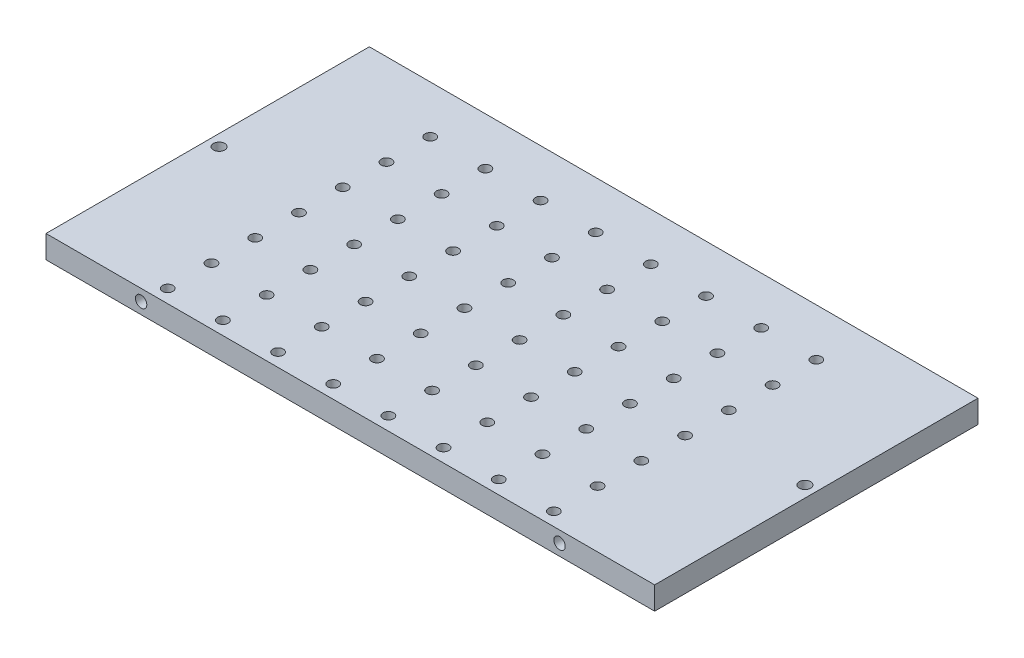
SolidWorks part; units mm, degrees
ref_plane "Plan de face" through (0, 0, 0) normal (0, 0, 1) x (1, 0, 0)
ref_plane "Plan de dessus" through (0, 0, 0) normal (0, 1, 0) x (1, 0, 0)
ref_plane "Plan de droite" through (0, 0, 0) normal (1, 0, 0) x (0, 0, -1)
sketch "Esquisse1" plane through (0, 0, 0) normal (0, 1, 0) x (1, 0, 0)
  line L1 (-80, -42.5) -> (80, -42.5)
  line L2 (-80, -42.5) -> (-80, 42.5)
  line L3 (-80, 42.5) -> (80, 42.5)
  line L4 (80, -42.5) -> (80, 42.5)
  line L5 (-80, -42.5) -> (80, 42.5) construction
  line L6 (-80, 42.5) -> (80, -42.5) construction
  point P0 (0, 0)
  dimension "D1" = 85
  dimension "D2" = 160
extrude "Boss.-Extru.1" add sketch "Esquisse1" along normal blind 6
sketch "Esquisse2" plane through (0, 0, 42.5) normal (0, 0, 1) x (1, 0, 0)
  line L0 (-80, 3) -> (29.6548, 3) construction
  line L3 (-80, 6) -> (-80, 0) construction
  line L5 (0, 0) -> (0, 17.0048) construction
  circle A0 centre (-55, 3) radius 1.5
  circle A1 centre (55, 3) radius 1.5
  dimension "D2" = 25
  dimension "D3" = 3
extrude "Enlèv. mat.-Extru.1" cut sketch "Esquisse2" against normal up to surface (85 mm away) up to face at (0, 3, -42.5)
sketch "Esquisse3" plane through (0, 0, 0) normal (0, 1, 0) x (1, 0, 0)
  line L1 (-55, 3.5) -> (10, 3.5) construction
  line L2 (-55, 3.5) -> (-55, 33.5) construction
  line L3 (-55, 33.5) -> (10, 33.5) construction
  line L4 (10, 3.5) -> (10, 33.5) construction
  line L5 (-55, 3.5) -> (10, 33.5) construction
  line L6 (-55, 33.5) -> (10, 3.5) construction
  line L7 (80, 42.5) -> (-80, 42.5) construction
  line L8 (-80, 42.5) -> (-80, -42.5) construction
  circle A0 centre (-51.5, 30) radius 1.375
  point P0 (-22.5, 18.5)
  dimension "D3" = 2.75
  dimension "D4" = 3.5
  dimension "D1" = 65
  dimension "D2" = 30
  dimension "D5" = 3.5
  dimension "D6" = 9
  dimension "D7" = 25
extrude "Enlèv. mat.-Extru.2" cut sketch "Esquisse3" along normal up to surface (6 mm away) up to face at (0, 6, 0)
pattern_linear "Répétition linéaire1" count 7 spacing 11.5 along (0, 0, 1) count 8 spacing 14.5 along (1, 0, 0) of "Enlèv. mat.-Extru.2"
sketch "Esquisse4" plane through (0, 0, 0) normal (0, 1, 0) x (1, 0, 0)
  line L0 (0, 42.5) -> (0, -48.0193) construction
  line L1 (80, 42.5) -> (-80, 42.5) construction
  line L2 (-80, 0) -> (96.9461, 0) construction
  line L3 (-80, 42.5) -> (-80, -42.5) construction
  circle A0 centre (-77, 0) radius 1.5
  circle A1 centre (77, 0) radius 1.5
  dimension "D1" = 3
  dimension "D2" = 3
extrude "Enlèv. mat.-Extru.3" cut sketch "Esquisse4" along normal up to surface (6 mm away) up to face at (-51.5, 6, -19.875)
fillet "Congé1" [suppressed] radius 1
